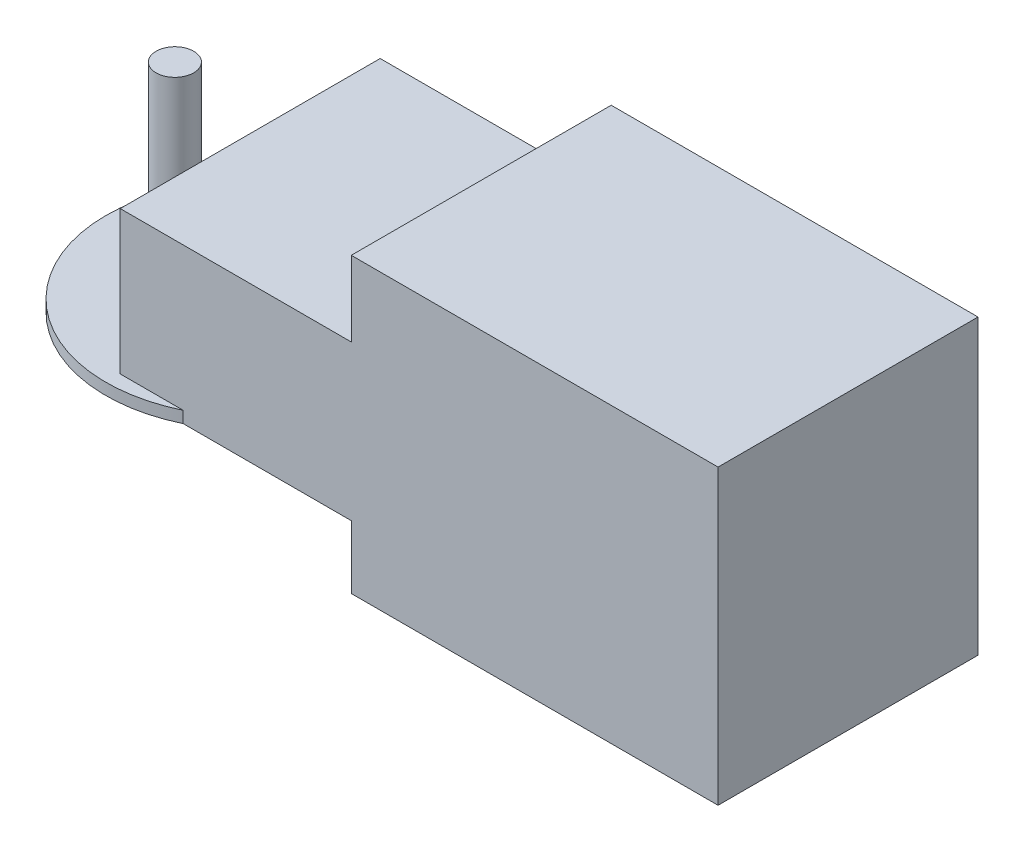
SolidWorks part; units mm, degrees
ref_plane "Front Plane" through (0, 0, 0) normal (0, 0, 1) x (1, 0, 0)
ref_plane "Top Plane" through (0, 0, 0) normal (0, 1, 0) x (1, 0, 0)
ref_plane "Right Plane" through (0, 0, 0) normal (1, 0, 0) x (0, 0, -1)
sketch "Sketch1" plane through (0, 0, 0) normal (0, 0, 1) x (1, 0, 0)
  line L0 (0, 1.2775) -> (0, 41.9175) construction
  line L1 (0, 52.0775) -> (67.1648, 52.0775) construction
  line L2 (1000, 31.7575) -> (5.8659, 31.7575) construction
  line L3 (-21.2638, 5.0875) -> (-5.08, 33.1186)
  line L4 (5.08, 33.1186) -> (21.2638, 5.0875)
  line L5 (-21.2638, 5.0875) -> (-26.3438, 5.0875)
  line L6 (-26.3438, 5.0875) -> (-26.3438, 6.8655)
  line L7 (-26.3438, 6.8655) -> (-31.75, 6.8655)
  line L8 (-31.75, 6.8655) -> (-31.75, 1.2775)
  line L9 (-31.75, 1.2775) -> (31.75, 1.2775)
  line L10 (31.75, 6.8655) -> (31.75, 1.2775)
  line L11 (26.3438, 6.8655) -> (31.75, 6.8655)
  line L12 (26.3438, 5.0875) -> (26.3438, 6.8655)
  line L13 (21.2638, 5.0875) -> (26.3438, 5.0875)
  line L14 (-5.8659, 31.7575) -> (-18.71, 31.7575) construction
  line L15 (-31.75, 6.8655) -> (-31.75, 57.5788)
  line L16 (31.75, 6.8655) -> (31.75, 57.5788)
  line L17 (31.75, 57.5788) -> (-31.75, 57.5788)
  arc A0 (5.08, 33.1186) -> (-5.08, 33.1186) centre (0, 41.9175) ccw
  point P18 (0, 1.2775)
  dimension "D1" = 30.48
  dimension "D2" = 20.32
  dimension "D3" = 60
  dimension "D4" = 63.5
  dimension "D5" = 5.08
  dimension "D6" = 3.81
  dimension "D7" = 5.588
extrude "Boss-Extrude2" add sketch "Sketch1" along normal blind 40 contours A0 L4 L13 L12 L11 L16 L17 L15 L7 L6 L5 L3
sketch "Sketch3" plane through (0, 0, 40) normal (0, 0, 1) x (1, 0, 0)
  line L0 (-31.75, 6.8655) -> (-31.75, 57.5788)
  line L1 (-31.75, 57.5788) -> (31.75, 57.5788)
  line L2 (31.75, 57.5788) -> (-31.75, 57.5788) construction
  line L3 (31.75, 57.5788) -> (31.75, 6.8655)
  line L4 (31.75, 6.8655) -> (-31.75, 6.8655)
extrude "Boss-Extrude3" add sketch "Sketch3" along normal blind 5
sketch "Sketch5" plane through (0, 0, 45) normal (0, 0, 1) x (1, 0, 0)
  line L0 (-31.75, 57.5788) -> (-31.75, 6.8655) construction
  line L1 (-71.75, 44.5841) -> (-31.75, 44.5841)
  line L2 (-71.75, 44.5841) -> (-71.75, 17.7888)
  line L3 (-71.75, 17.7888) -> (-31.75, 17.7888)
  line L4 (-31.75, 44.5841) -> (-31.75, 17.7888)
  dimension "D1" = 40
  dimension "D2" = 26.7954
extrude "Boss-Extrude4" add sketch "Sketch5" against normal blind 45 contours L1 L4 L3 L2
sketch "Sketch7" plane through (0, 17.7888, 0) normal (0, -1, 0) x (1, 0, 0)
  line L0 (-71.75, 0) -> (-71.75, 45) construction
  circle A0 centre (-71.75, 22.5) radius 25
  dimension "D1" = 50
extrude "Boss-Extrude6" add sketch "Sketch7" against normal blind 2
sketch "Sketch11" plane through (0, 17.7888, 0) normal (0, -1, 0) x (-1, 0, 0)
  line L0 (31.75, -22.5) -> (96.75, -22.5) construction
  line L1 (31.75, 0) -> (31.75, -45) construction
  line L2 (71.75, -47.5) -> (71.75, 2.5) construction
  arc A0 (60.8528, -45) -> (60.8528, 0) centre (71.75, -22.5) ccw construction
  circle A1 centre (84.7851, -22.5) radius 6
  dimension "D1" = 12
extrude "Boss-Extrude7" add sketch "Sketch11" against normal blind 6 contours A1
sketch "Sketch13" plane through (0, 23.7888, 0) normal (0, 1, 0) x (1, 0, 0)
  circle A0 centre (-84.7851, -22.5) radius 3.25
  dimension "D1" = 6.5
extrude "Boss-Extrude8" add sketch "Sketch13" along normal blind 25
